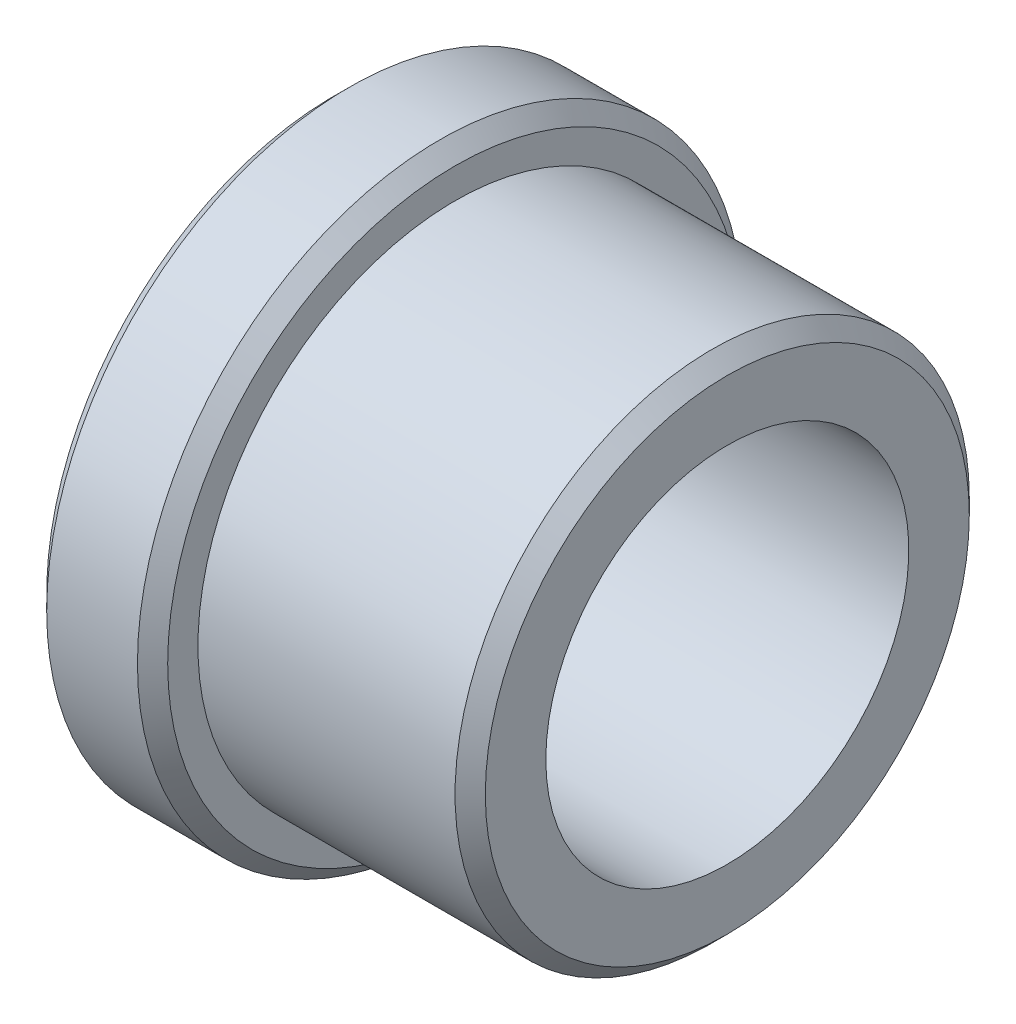
SolidWorks part; units mm, degrees
ref_plane "前视基准面" through (0, 0, 0) normal (0, 0, 1) x (1, 0, 0)
ref_plane "上视基准面" through (0, 0, 0) normal (0, 1, 0) x (1, 0, 0)
ref_plane "右视基准面" through (0, 0, 0) normal (1, 0, 0) x (0, 0, -1)
other "Configuration Table"
sketch "草图1" plane through (0, 0, 0) normal (1, 0, 0) x (0, 0, -1)
  circle A0 centre (0, 0) radius 10
  circle A1 centre (0, 0) radius 6
  dimension "D1" = 20
  dimension "D2" = 12
extrude "凸台-拉伸2" add sketch "草图1" along normal blind 13
sketch "草图2" plane through (13, 0, 0) normal (1, 0, 0) x (0, 0, -1)
  circle A0 centre (0, 0) radius 8.5
  dimension "D1" = 17
extrude "切除-拉伸1" cut sketch "草图2" against normal blind 9 flip side to cut
chamfer "倒角1" distance 0.5 angle 45 4 edges at (0, 0, -6) (0, 0, -10) (4, 0, -10) (13, 0, -8.5)
